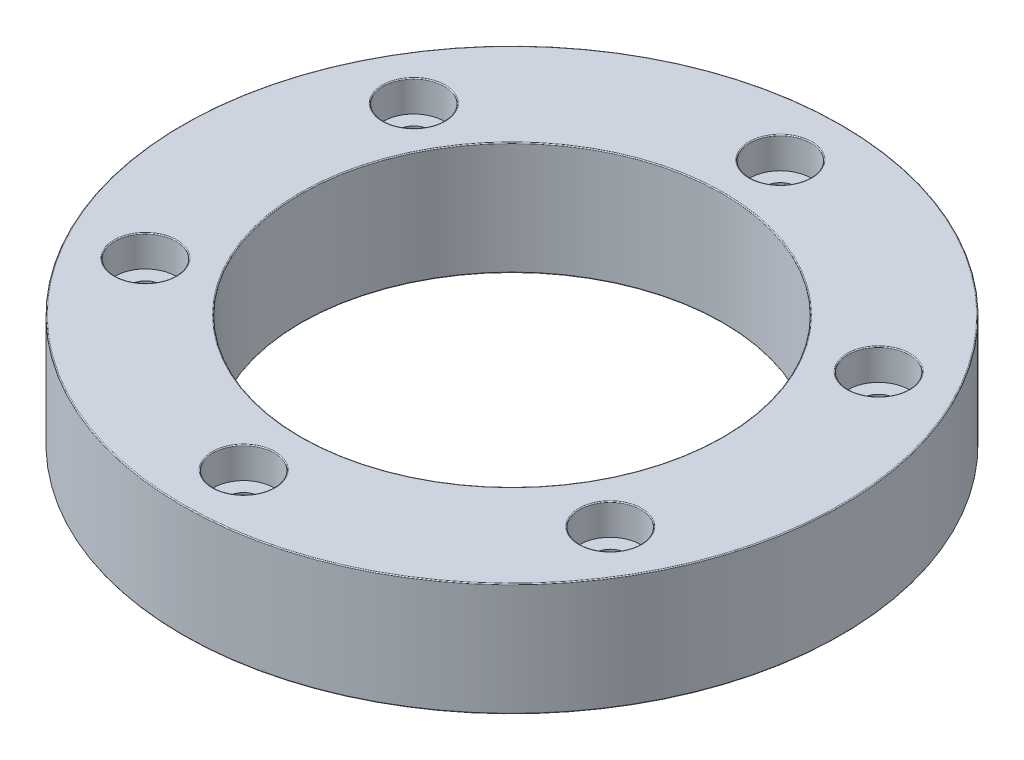
SolidWorks part; units mm, degrees
material "Plain Carbon Steel"
ref_plane "Front Plane" through (0, 0, 0) normal (0, 0, 1) x (1, 0, 0)
ref_plane "Top Plane" through (0, 0, 0) normal (0, 1, 0) x (1, 0, 0)
ref_plane "Right Plane" through (0, 0, 0) normal (1, 0, 0) x (0, 0, -1)
sketch "Sketch1" plane through (0, 0, 0) normal (0, 1, 0) x (1, 0, 0)
  circle A0 centre (0, 0) radius 22.4
  circle A1 centre (0, 0) radius 35
  dimension "D1" = 44.8
  dimension "D2" = 70
extrude "Boss-Extrude1" add sketch "Sketch1" along normal blind 12
sketch "Sketch2" plane through (0, 12, 0) normal (0, 1, 0) x (1, 0, 0)
  circle A0 centre (0, 0) radius 28.5
  circle A1 centre (0, 28.5) radius 3.25
  circle A2 centre (24.6817, 14.25) radius 3.25
  circle A3 centre (24.6817, -14.25) radius 3.25
  circle A4 centre (0, -28.5) radius 3.25
  circle A5 centre (-24.6817, -14.25) radius 3.25
  circle A6 centre (-24.6817, 14.25) radius 3.25
  point P18 (0, 0)
  dimension "D1" = 57
  dimension "D2" = 6.5
  dimension "D3" = 6
extrude "Cut-Extrude1" cut sketch "Sketch2" against normal blind 3.3 contours A3 | A2 | A1 | A6 | A5 | A4
sketch "Sketch3" plane through (0, 12, 0) normal (0, 1, 0) x (1, 0, 0)
  circle A0 centre (0, 0) radius 28.5
  circle A1 centre (0, 28.5) radius 1.7
  circle A2 centre (24.6817, 14.25) radius 1.7
  circle A3 centre (24.6817, -14.25) radius 1.7
  circle A4 centre (0, -28.5) radius 1.7
  circle A5 centre (-24.6817, -14.25) radius 1.7
  circle A6 centre (-24.6817, 14.25) radius 1.7
  point P19 (0, 0)
  dimension "D1" = 3.4
  dimension "D2" = 6
extrude "Cut-Extrude2" cut sketch "Sketch3" against normal up to surface (12 mm away) contours A6 | A1 | A2 | A3 | A4 | A5 up to face at (0, 0, 35)
fillet "Fillet1" radius 0.1 4 edges at (0, 0, 35) (0, 12, 35) (0, 0, 22.4) (0, 12, 22.4)
fillet "Fillet2" radius 0.1 6 edges at (-24.6817, 12, -11) (-24.6817, 12, 17.5) (0, 12, 31.75) (0, 12, -25.25) (24.6817, 12, -11) (24.6817, 12, 17.5)
